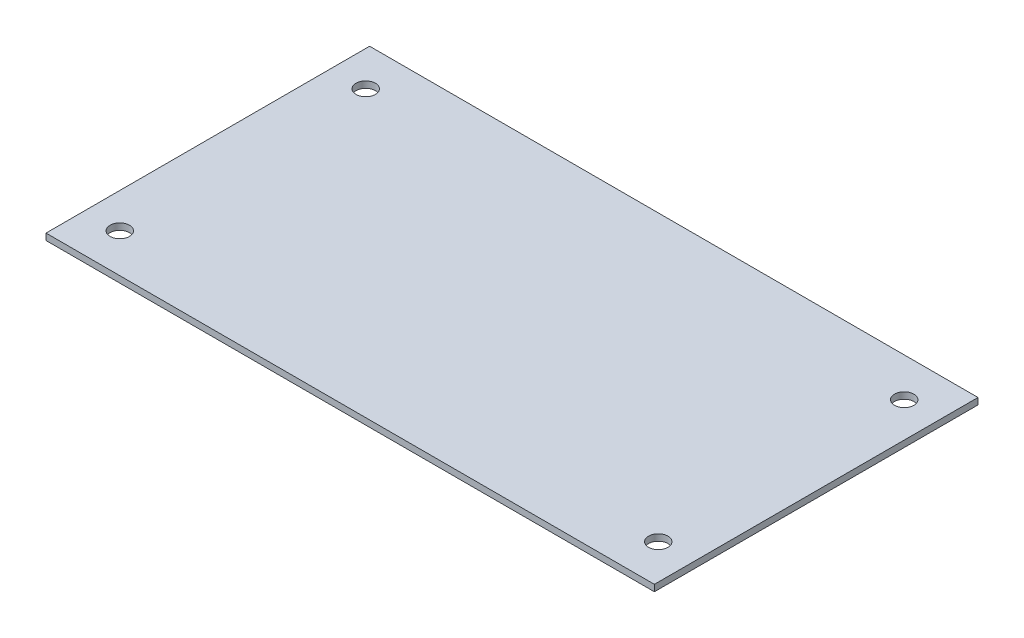
SolidWorks part; units mm, degrees
ref_plane "Plan de face" through (0, 0, 0) normal (0, 0, 1) x (1, 0, 0)
ref_plane "Plan de dessus" through (0, 0, 0) normal (0, 1, 0) x (1, 0, 0)
ref_plane "Plan de droite" through (0, 0, 0) normal (1, 0, 0) x (0, 0, -1)
sketch "Esquisse1" plane through (0, 0, 0) normal (0, 1, 0) x (1, 0, 0)
  line L0 (0, 0) -> (0, 25) construction
  line L1 (-47, -25) -> (47, -25)
  line L2 (-47, -25) -> (-47, 25)
  line L3 (-47, 25) -> (47, 25)
  line L4 (47, -25) -> (47, 25)
  line L5 (-47, -25) -> (47, 25) construction
  line L6 (-47, 25) -> (47, -25) construction
  line L7 (0, 0) -> (47, 0) construction
  circle A0 centre (-41.6, 19) radius 1.5
  circle A1 centre (41.6, 19) radius 1.5
  circle A2 centre (41.6, -19) radius 1.5
  circle A3 centre (-41.6, -19) radius 1.5
  point P0 (0, 0)
  dimension "D3" = 3
  dimension "D1" = 94
  dimension "D2" = 50
  dimension "D4" = 38
  dimension "D5" = 83.2
extrude "Boss.-Extru.1" add sketch "Esquisse1" along normal blind 1
